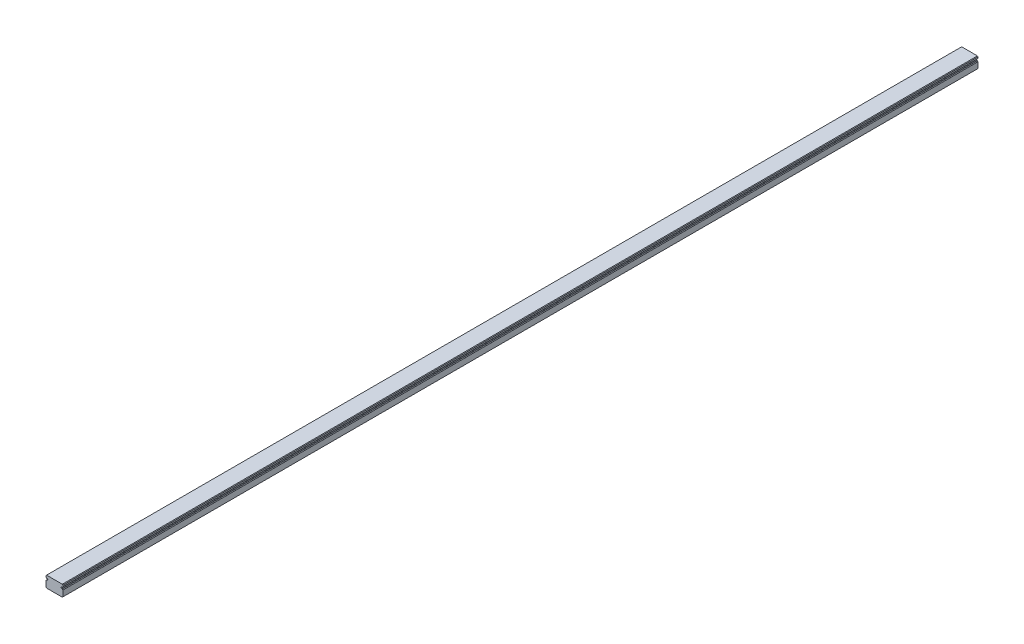
SolidWorks part; units mm, degrees
material "1.4000 (X6Cr13)"
ref_plane "Спереди" through (0, 0, 0) normal (0, 0, 1) x (1, 0, 0)
ref_plane "Сверху" through (0, 0, 0) normal (0, 1, 0) x (1, 0, 0)
ref_plane "Справа" through (0, 0, 0) normal (1, 0, 0) x (0, 0, -1)
sketch "Model" plane through (0, 0, 0) normal (0, 0, 1) x (1, 0, 0)
  line L1 (-6, -3.6269) -> (-5.6, -4.0269)
  line L2 (-6, 0.5731) -> (-6, -3.6269)
  line L3 (-5.9627, 0.6141) -> (-6, 0.5731)
  line L4 (-5.5, 1.1231) -> (-5.6068, 1.0057)
  line L5 (-5.2, 1.1231) -> (-5.5, 1.1231)
  line L6 (-5.5, 2.0231) -> (-5.2, 2.0231)
  line L7 (-5.6068, 2.1406) -> (-5.5, 2.0231)
  line L8 (-6, 2.5731) -> (-5.9627, 2.5321)
  line L9 (-6, 3.5731) -> (-6, 2.5731)
  line L10 (-5.6, 3.9731) -> (-6, 3.5731)
  line L11 (6, 3.5731) -> (5.6, 3.9731)
  line L12 (6, 2.5731) -> (6, 3.5731)
  line L13 (5.9627, 2.5321) -> (6, 2.5731)
  line L14 (5.5, 2.0231) -> (5.6068, 2.1406)
  line L15 (5.2, 2.0231) -> (5.5, 2.0231)
  line L16 (5.5, 1.1231) -> (5.2, 1.1231)
  line L17 (5.6068, 1.0057) -> (5.5, 1.1231)
  line L18 (6, 0.5731) -> (5.9627, 0.6141)
  line L19 (6, -3.6269) -> (6, 0.5731)
  line L20 (5.6, -4.0269) -> (6, -3.6269)
  line L21 (-5.6, -4.0269) -> (5.6, -4.0269)
  line L22 (5.6, 3.9731) -> (-5.6, 3.9731)
  line L23 (0, 3.9731) -> (0, 0) construction
  line L24 (0, 0) -> (0, -4.0269) construction
  arc A0 (-5.9627, 0.6141) -> (-5.6068, 1.0057) centre (-6.0067, 1.0117) ccw
  arc A1 (-5.2, 1.1231) -> (-5.2, 2.0231) centre (-5.2, 1.5731) ccw
  arc A2 (-5.6068, 2.1406) -> (-5.9627, 2.5321) centre (-6.0067, 2.1345) ccw
  arc A3 (5.9627, 2.5321) -> (5.6068, 2.1406) centre (6.0067, 2.1345) ccw
  arc A4 (5.2, 2.0231) -> (5.2, 1.1231) centre (5.2, 1.5731) ccw
  arc A5 (5.6068, 1.0057) -> (5.9627, 0.6141) centre (6.0067, 1.0117) ccw
extrude "База" add sketch "Model" against normal mid plane 650
